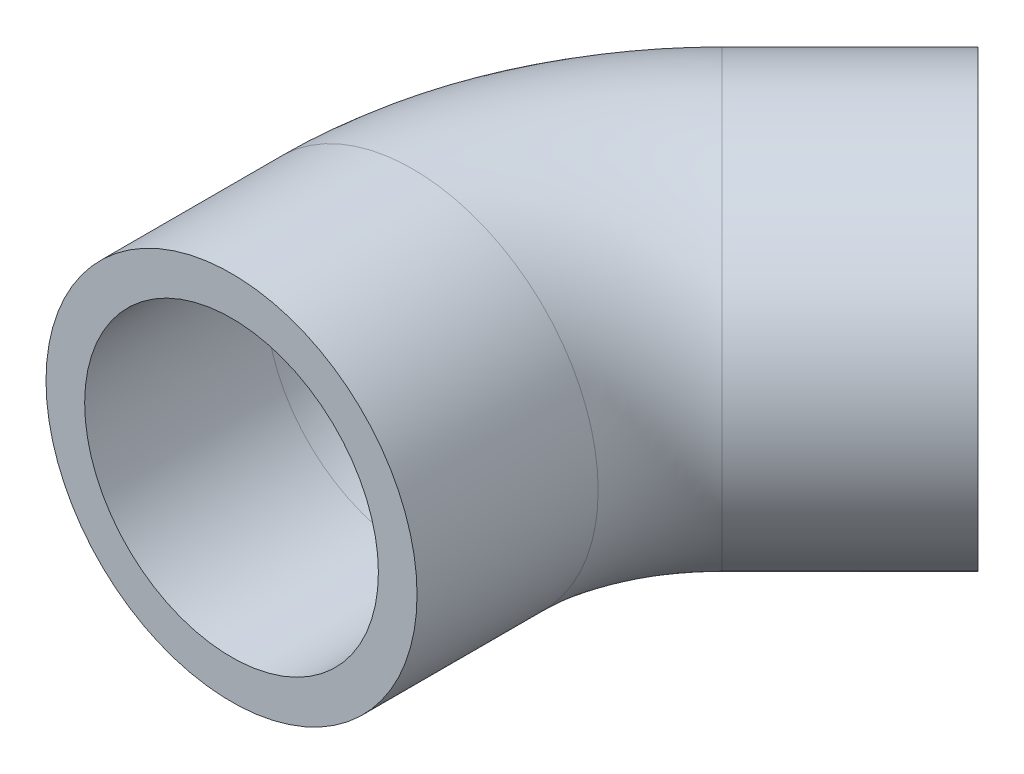
SolidWorks part; units mm, degrees
ref_plane "Front Plane" through (0, 0, 0) normal (0, 0, 1) x (1, 0, 0)
ref_plane "Top Plane" through (0, 0, 0) normal (0, 1, 0) x (1, 0, 0)
ref_plane "Right Plane" through (0, 0, 0) normal (1, 0, 0) x (0, 0, -1)
sketch "Sketch1" plane through (0, 0, 0) normal (0, 1, 0) x (1, 0, 0)
  line L0 (0, 0) -> (0, 29.758)
  line L1 (14.879, 65.679) -> (35.921, 86.721)
  arc A0 (0, 29.758) -> (14.879, 65.679) centre (50.8, 29.758) cw
  point P6 (0, 50.8)
  dimension "D4" = 50.8
  dimension "D1" = 135
  dimension "D2" = 50.8
  dimension "D3" = 50.8
sketch "Sketch2" plane through (0, 0, 0) normal (0, 0, 1) x (1, 0, 0)
  circle A0 centre (0, 0) radius 24.13
  circle A1 centre (0, 0) radius 30.48
  dimension "D1" = 48.26
  dimension "D2" = 6.35
sweep "Sweep1" add profiles "Sketch2" path "Sketch1"
